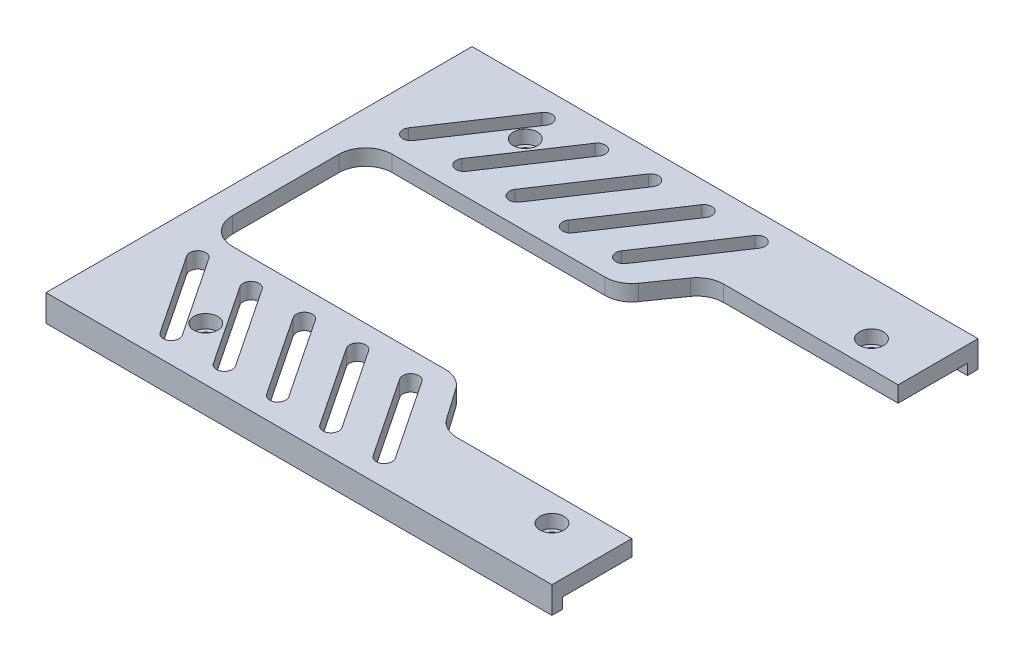
SolidWorks part; units mm, degrees
ref_plane "Front Plane" through (0, 0, 0) normal (0, 0, 1) x (1, 0, 0)
ref_plane "Top Plane" through (0, 0, 0) normal (0, 1, 0) x (1, 0, 0)
ref_plane "Right Plane" through (0, 0, 0) normal (1, 0, 0) x (0, 0, -1)
sketch "Sketch1" plane through (0, 0, 0) normal (0, 1, 0) x (1, 0, 0)
  line L1 (0, 0) -> (190, 0)
  line L2 (0, 0) -> (0, 160)
  line L3 (0, 160) -> (190, 160)
  line L4 (190, 0) -> (190, 160)
  dimension "D1" = 160
  dimension "D2" = 190
extrude "Boss-Extrude1" add sketch "Sketch1" along normal blind 6
sketch "Sketch2" plane through (0, 6, 0) normal (0, 1, 0) x (1, 0, 0)
  line L0 (10, 60) -> (10, 100)
  line L1 (20, 110) -> (68.3728, 110)
  line L2 (68.3728, 110) -> (100, 110)
  line L3 (108.1915, 114.2642) -> (116.224, 125.7358)
  line L4 (124.4155, 130) -> (190, 130)
  line L5 (190, 0) -> (190, 160) construction
  line L6 (20, 50) -> (100, 50)
  line L7 (108.1915, 45.7358) -> (116.224, 34.2642)
  line L8 (124.4155, 30) -> (190, 30)
  line L9 (190, 160) -> (0, 160) construction
  line L10 (0, 160) -> (0, 0) construction
  line L11 (0, 0) -> (190, 0) construction
  line L13 (97, 40) -> (77, 40)
  line L14 (77, 40) -> (57, 40)
  line L15 (57, 40) -> (37, 40)
  line L16 (37, 40) -> (17, 40)
  line L17 (37, 0) -> (37, 10)
  line L18 (37, 10) -> (57, 10)
  line L19 (57, 10) -> (77, 10)
  line L20 (77, 10) -> (97, 10)
  line L21 (97, 10) -> (117, 10)
  line L22 (17, 40) -> (37, 10) construction
  line L23 (19.4962, 41.6641) -> (39.4962, 11.6641)
  line L24 (14.5038, 38.3359) -> (34.5038, 8.3359)
  line L25 (37, 40) -> (57, 10) construction
  line L26 (39.4962, 41.6641) -> (59.4962, 11.6641)
  line L27 (34.5038, 38.3359) -> (54.5038, 8.3359)
  line L28 (57, 40) -> (77, 10) construction
  line L29 (59.4962, 41.6641) -> (79.4962, 11.6641)
  line L30 (54.5038, 38.3359) -> (74.5038, 8.3359)
  line L31 (77, 40) -> (97, 10) construction
  line L32 (79.4962, 41.6641) -> (99.4962, 11.6641)
  line L33 (74.5038, 38.3359) -> (94.5038, 8.3359)
  line L34 (97, 40) -> (117, 10) construction
  line L35 (99.4962, 41.6641) -> (119.4962, 11.6641)
  line L36 (94.5038, 38.3359) -> (114.5038, 8.3359)
  line L37 (0, 80) -> (204.0102, 80) construction
  line L38 (97, 120) -> (117, 150) construction
  line L39 (99.4962, 118.3359) -> (119.4962, 148.3359)
  line L40 (94.5038, 121.6641) -> (114.5038, 151.6641)
  line L41 (77, 120) -> (97, 150) construction
  line L42 (79.4962, 118.3359) -> (99.4962, 148.3359)
  line L43 (74.5038, 121.6641) -> (94.5038, 151.6641)
  line L44 (57, 120) -> (77, 150) construction
  line L45 (59.4962, 118.3359) -> (79.4962, 148.3359)
  line L46 (54.5038, 121.6641) -> (74.5038, 151.6641)
  line L47 (37, 120) -> (57, 150) construction
  line L48 (39.4962, 118.3359) -> (59.4962, 148.3359)
  line L49 (34.5038, 121.6641) -> (54.5038, 151.6641)
  line L50 (17, 120) -> (37, 150) construction
  line L51 (19.4962, 118.3359) -> (39.4962, 148.3359)
  line L52 (14.5038, 121.6641) -> (34.5038, 151.6641)
  arc A0 (19.4962, 41.6641) -> (14.5038, 38.3359) centre (17, 40) ccw
  arc A1 (34.5038, 8.3359) -> (39.4962, 11.6641) centre (37, 10) ccw
  arc A2 (39.4962, 41.6641) -> (34.5038, 38.3359) centre (37, 40) ccw
  arc A3 (54.5038, 8.3359) -> (59.4962, 11.6641) centre (57, 10) ccw
  arc A4 (59.4962, 41.6641) -> (54.5038, 38.3359) centre (57, 40) ccw
  arc A5 (74.5038, 8.3359) -> (79.4962, 11.6641) centre (77, 10) ccw
  arc A6 (79.4962, 41.6641) -> (74.5038, 38.3359) centre (77, 40) ccw
  arc A7 (94.5038, 8.3359) -> (99.4962, 11.6641) centre (97, 10) ccw
  arc A8 (99.4962, 41.6641) -> (94.5038, 38.3359) centre (97, 40) ccw
  arc A9 (114.5038, 8.3359) -> (119.4962, 11.6641) centre (117, 10) ccw
  arc A10 (124.4155, 130) -> (116.224, 125.7358) centre (124.4155, 120) ccw
  arc A11 (108.1915, 114.2642) -> (100, 110) centre (100, 120) cw
  arc A12 (20, 110) -> (10, 100) centre (20, 100) ccw
  arc A13 (10, 60) -> (20, 50) centre (20, 60) ccw
  arc A14 (116.224, 34.2642) -> (124.4155, 30) centre (124.4155, 40) ccw
  arc A15 (108.1915, 45.7358) -> (100, 50) centre (100, 40) ccw
  arc A16 (99.4962, 118.3359) -> (94.5038, 121.6641) centre (97, 120) cw
  arc A17 (114.5038, 151.6641) -> (119.4962, 148.3359) centre (117, 150) cw
  arc A18 (79.4962, 118.3359) -> (74.5038, 121.6641) centre (77, 120) cw
  arc A19 (94.5038, 151.6641) -> (99.4962, 148.3359) centre (97, 150) cw
  arc A20 (59.4962, 118.3359) -> (54.5038, 121.6641) centre (57, 120) cw
  arc A21 (74.5038, 151.6641) -> (79.4962, 148.3359) centre (77, 150) cw
  arc A22 (39.4962, 118.3359) -> (34.5038, 121.6641) centre (37, 120) cw
  arc A23 (54.5038, 151.6641) -> (59.4962, 148.3359) centre (57, 150) cw
  arc A24 (19.4962, 118.3359) -> (14.5038, 121.6641) centre (17, 120) cw
  arc A25 (34.5038, 151.6641) -> (39.4962, 148.3359) centre (37, 150) cw
  point P25 (27, 25)
  point P34 (47, 25)
  point P39 (67, 25)
  point P44 (87, 25)
  point P49 (107, 25)
  point P56 (119.2098, 130)
  point P59 (105.2057, 110)
  point P64 (10, 50)
  point P67 (119.2098, 30)
  point P75 (107, 135)
  point P82 (87, 135)
  point P89 (67, 135)
  point P96 (47, 135)
  point P103 (27, 135)
  dimension "D22" = 3
  dimension "D23" = 3
  dimension "D24" = 3
  dimension "D25" = 3
  dimension "D26" = 3
  dimension "D27" = 10
  dimension "D8" = 90
  dimension "D29" = 10
  dimension "D1" = 10
  dimension "D2" = 30
  dimension "D3" = 30
  dimension "D4" = 125
  dimension "D5" = 125
  dimension "D6" = 50
  dimension "D7" = 50
  dimension "D9" = 90
  dimension "D10" = 70.7902
  dimension "D11" = 70.7902
  dimension "D12" = 20
  dimension "D13" = 20
  dimension "D14" = 20
  dimension "D15" = 20
  dimension "D16" = 10
  dimension "D17" = 10
  dimension "D18" = 20
  dimension "D19" = 20
  dimension "D20" = 20
  dimension "D21" = 20
  dimension "D28" = 3
  dimension "D30" = 90
  dimension "D31" = 7.6833
  dimension "D32" = 10.641
  dimension "D33" = 10.641
  dimension "D34" = 10.641
  dimension "D35" = 10.641
extrude "Cut-Extrude1" cut sketch "Sketch2" against normal blind 10
sketch "Sketch3" plane through (0, 0, 0) normal (0, -1, 0) x (1, 0, 0)
  line L0 (0, -160) -> (0, 0) construction
  line L1 (190, -160) -> (0, -160)
  line L2 (190, -160) -> (190, -156)
  line L3 (190, -156) -> (0, -156)
  line L4 (0, -160) -> (0, -156)
  line L5 (0, 0) -> (190, 0) construction
  line L6 (0, -160) -> (5, -160)
  line L7 (0, -160) -> (0, 0)
  line L8 (0, 0) -> (5, 0)
  line L9 (5, -160) -> (5, 0)
  line L11 (0, -4) -> (190, -4)
  line L12 (0, -4) -> (0, 0)
  line L13 (0, 0) -> (190, 0)
  line L14 (190, -4) -> (190, 0)
  dimension "D1" = 4
  dimension "D2" = 5
  dimension "D3" = 4
extrude "Boss-Extrude3" add sketch "Sketch3" along normal blind 4 contours L9 L1 L2 L3 | L1 L9 L3 L4 | L11 L7 L3 L9 | L11 L14 L13 L9 | L7 L11 L9 L8
sketch "Sketch4" plane through (0, 6, 0) normal (0, 1, 0) x (1, 0, 0)
  line L0 (0, 80) -> (218.0828, 80) construction
  line L1 (0, 160) -> (0, 0) construction
  line L2 (190, 160) -> (0, 160) construction
  circle A0 centre (170, 140) radius 4.5
  circle A1 centre (40, 140) radius 4.5
  circle A2 centre (170, 20) radius 4.5
  circle A3 centre (40, 20) radius 4.5
  dimension "D2" = 9
  dimension "D3" = 9
  dimension "D4" = 170
  dimension "D5" = 40
  dimension "D6" = 20
  dimension "D1" = 20
extrude "Cut-Extrude2" cut sketch "Sketch4" against normal blind 5
sketch "Sketch5" plane through (0, 0, 0) normal (0, 1, 0) x (1, 0, 0)
  line L0 (0, 80) -> (218.0828, 80) construction
  line L2 (0, 160) -> (0, 0) construction
  circle A0 centre (170, 140) radius 3
  circle A1 centre (40, 140) radius 3
  circle A2 centre (170, 20) radius 3
  circle A3 centre (40, 20) radius 3
  dimension "D2" = 6
  dimension "D3" = 6
  dimension "D1" = 170
extrude "Cut-Extrude7" cut sketch "Sketch5" along normal blind 5
